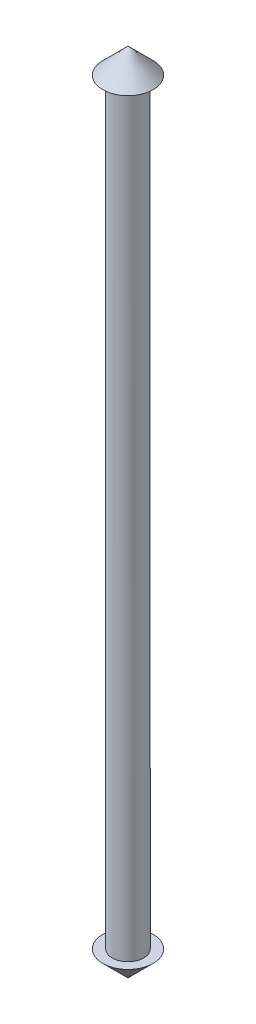
SolidWorks part; units mm, degrees
material "Copper"
ref_plane "Front Plane" through (0, 0, 0) normal (0, 0, 1) x (1, 0, 0)
ref_plane "Top Plane" through (0, 0, 0) normal (0, 1, 0) x (1, 0, 0)
ref_plane "Right Plane" through (0, 0, 0) normal (1, 0, 0) x (0, 0, -1)
sketch "Sketch1" plane through (0, 0, 0) normal (0, 1, 0) x (1, 0, 0)
  circle A0 centre (0, 0) radius 2.5
  dimension "D1" = 5
extrude "Boss-Extrude1" add sketch "Sketch1" along normal mid plane 120
sketch "Sketch2" plane through (0, 60, 0) normal (0, 1, 0) x (1, 0, 0)
  circle A0 centre (0, 0) radius 4
  dimension "D1" = 8
extrude "Boss-Extrude2" add sketch "Sketch2" along normal blind 6 draft 45 separate body
mirror "Mirror1" about plane through (0, 0, 0) normal (0, 1, 0) of bodies 102
combine bodies "Combine1" operation type add bodies to combine 101 102 103
